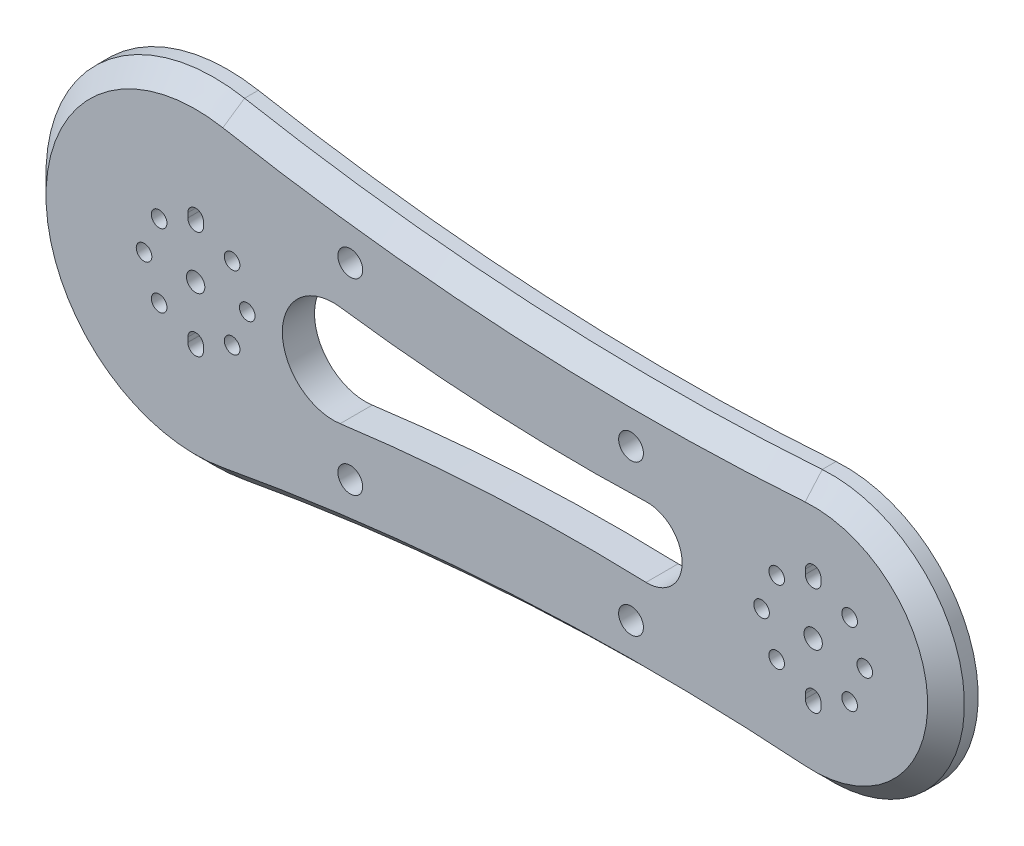
SolidWorks part; units mm, degrees
ref_plane "Front Plane" through (0, 0, 0) normal (0, 0, 1) x (1, 0, 0)
ref_plane "Top Plane" through (0, 0, 0) normal (0, 1, 0) x (1, 0, 0)
ref_plane "Right Plane" through (0, 0, 0) normal (1, 0, 0) x (0, 0, -1)
sketch "Sketch1" plane through (0, 0, 0) normal (0, 0, 1) x (1, 0, 0)
  line L0 (-17.0864, 0) -> (182.9136, 0)
  arc A0 (26.1506, 35.9768) -> (26.1506, -35.9768) centre (19.5, 0) ccw
  arc A1 (151.9551, -28.8671) -> (151.9551, 28.8671) centre (153.9759, 0) ccw
  arc A2 (26.1506, 35.9768) -> (151.9551, 28.8671) centre (117.0401, 527.6466) ccw
  arc A3 (26.1506, -35.9768) -> (151.9551, -28.8671) centre (117.0401, -527.6466) cw
  circle A4 centre (19.5, 7) radius 1.7
  circle A5 centre (26.5, 0) radius 1.7
  circle A6 centre (12.5, 0) radius 1.7
  circle A7 centre (19.5, -7) radius 1.7
  circle A8 centre (19.5, 0) radius 2
  circle A9 centre (153.9759, 0) radius 2
extrude "Boss-Extrude1" add sketch "Sketch1" along normal blind 7 contours A9 L0 A1 A2 A0 A6 A8 A5 A4 | A9 L0 A5 A8 A6 A0 A3 A1 A7
chamfer "Chamfer1" distance 4 angle 45 4 edges at (-17.0864, 0, 7) (88.828, -28.4431, 7) (182.9136, 0, 7) (88.828, 28.4431, 7)
sketch "Sketch3" plane through (0, 0, 7) normal (0, 0, 1) x (1, 0, 0)
  line L0 (19.5, 0) -> (38.3853, 0)
  arc A0 (50.964, 10.9877) -> (50.964, -10.9877) centre (49.4737, 0) ccw
  arc A1 (117.5751, -7.61) -> (117.5751, 7.61) centre (117.83, 0) ccw
  arc A2 (50.964, 10.9877) -> (117.5751, 7.61) centre (104.2918, 404.1499) ccw
  arc A3 (50.964, -10.9877) -> (117.5751, -7.61) centre (104.2918, -404.1499) cw
extrude "Cut-Extrude2" cut sketch "Sketch3" against normal blind 23 contours A0 A3 A1 A2
sketch "Sketch4" plane through (0, 0, 0) normal (0, 0, -1) x (-1, 0, 0)
  circle A0 centre (-114.3134, 16.4208) radius 2.7
  circle A1 centre (-53.1777, 20.4349) radius 2.7
  circle A2 centre (-114.3134, -16.4208) radius 2.7
  circle A3 centre (-53.1777, -20.4349) radius 2.7
extrude "Cut-Extrude3" cut sketch "Sketch4" against normal blind 37
sketch "Sketch5" plane through (0, 0, 0) normal (0, 0, -1) x (-1, 0, 0)
  circle A0 centre (-19.5, -11.235) radius 1.7
  circle A1 centre (-11.5557, -7.9443) radius 1.7
  circle A2 centre (-8.265, 0) radius 1.7
  circle A3 centre (-11.5557, 7.9443) radius 1.7
  circle A4 centre (-19.5, 11.235) radius 1.7
  circle A5 centre (-27.4443, 7.9443) radius 1.7
  circle A6 centre (-30.735, 0) radius 1.7
  circle A7 centre (-27.4443, -7.9443) radius 1.7
extrude "Cut-Extrude4" cut sketch "Sketch5" against normal blind 29.5
sketch "Sketch6" plane through (0, 0, 7) normal (0, 0, 1) x (1, 0, 0)
  circle A0 centre (19.5, 7) radius 1.7
  circle A1 centre (26.5, 0) radius 1.7
  circle A2 centre (19.5, -7) radius 1.7
  circle A3 centre (12.5, 0) radius 1.7
extrude "Boss-Extrude2" add sketch "Sketch6" against normal up to surface (7 mm away) up to face at (25.7443, -7.9443, 0)
sketch "Sketch7" plane through (0, 0, 0) normal (0, 0, -1) x (-1, 0, 0)
  circle A0 centre (-146.0315, -7.9443) radius 1.7
  circle A1 centre (-153.9759, -11.235) radius 1.7
  circle A2 centre (-161.9202, -7.9443) radius 1.7
  circle A3 centre (-165.2109, 0) radius 1.7
  circle A4 centre (-161.9202, 7.9443) radius 1.7
  circle A5 centre (-153.9759, 11.235) radius 1.7
  circle A6 centre (-146.0315, 7.9443) radius 1.7
  circle A7 centre (-142.7409, 0) radius 1.7
extrude "Cut-Extrude5" cut sketch "Sketch7" against normal blind 29.5
sketch "Sketch9" plane through (0, 0, 7) normal (0, 0, 1) x (1, 0, 0)
  line L0 (153.9759, 11.235) -> (153.9759, 12.235) construction
  line L1 (152.2759, 11.235) -> (152.2759, 12.235)
  line L2 (155.6759, 11.235) -> (155.6759, 12.235)
  line L3 (153.9759, -11.235) -> (153.9759, -12.235) construction
  line L4 (155.6759, -11.235) -> (155.6759, -12.235)
  line L5 (152.2759, -11.235) -> (152.2759, -12.235)
  line L6 (19.5, 0) -> (153.9759, 0)
  line L7 (86.7379, 0) -> (86.7379, 2.5183)
  line L8 (19.5, 11.235) -> (19.5, 12.235) construction
  line L9 (21.2, 11.235) -> (21.2, 12.235)
  line L10 (17.8, 11.235) -> (17.8, 12.235)
  line L11 (19.5, -11.235) -> (19.5, -12.235) construction
  line L12 (17.8, -11.235) -> (17.8, -12.235)
  line L13 (21.2, -11.235) -> (21.2, -12.235)
  arc A0 (152.2759, 11.235) -> (155.6759, 11.235) centre (153.9759, 11.235) ccw
  arc A1 (155.6759, 12.235) -> (152.2759, 12.235) centre (153.9759, 12.235) ccw
  arc A2 (155.6759, -11.235) -> (152.2759, -11.235) centre (153.9759, -11.235) ccw
  arc A3 (152.2759, -12.235) -> (155.6759, -12.235) centre (153.9759, -12.235) ccw
  arc A4 (21.2, 11.235) -> (17.8, 11.235) centre (19.5, 11.235) cw
  arc A5 (17.8, 12.235) -> (21.2, 12.235) centre (19.5, 12.235) cw
  arc A6 (17.8, -11.235) -> (21.2, -11.235) centre (19.5, -11.235) cw
  arc A7 (21.2, -12.235) -> (17.8, -12.235) centre (19.5, -12.235) cw
  point P3 (153.9759, 11.735)
  point P11 (153.9759, -11.735)
  point P24 (19.5, 11.735)
  point P31 (19.5, -11.735)
  circle M8 centre (153.9759, -11.235) radius 1.7
  circle M12 centre (153.9759, 11.235) radius 1.7
  circle M19 centre (19.5, 11.235) radius 1.7
  circle M23 centre (19.5, -11.235) radius 1.7
  dimension "D3" = 1.7
  dimension "D4" = 1.7
  dimension "D1" = 1
  dimension "D2" = 1
extrude "Cut-Extrude6" cut sketch "Sketch9" against normal blind 10 contours L2 A1 L1 M12 | M12 | L5 A3 L4 M8 | M8 | A5 L10 L9 M19 | M19 | M23 | A7 L13 L12 M23
